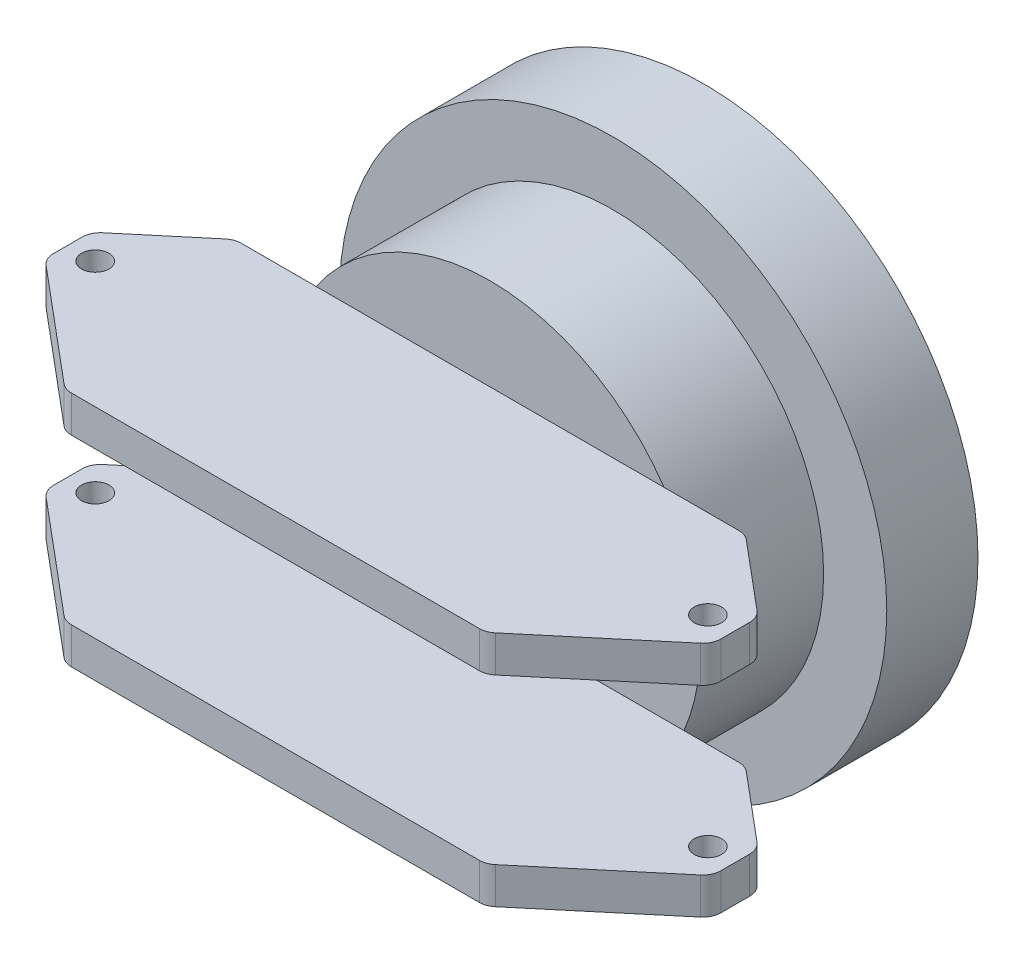
SolidWorks part; units mm, degrees
material "AISI 347 Annealed Stainless Steel (SS)"
ref_plane "Front" through (0, 0, 0) normal (0, 0, 1) x (1, 0, 0)
ref_plane "Top" through (0, 0, 0) normal (0, 1, 0) x (1, 0, 0)
ref_plane "Right" through (0, 0, 0) normal (1, 0, 0) x (0, 0, -1)
sketch "Sketch1" plane through (0, 0, 0) normal (0, 0, 1) x (1, 0, 0)
  circle A0 centre (0, 0) radius 30
  dimension "D1" = 60
extrude "Boss-Extrude1" add sketch "Sketch1" along normal blind 10
sketch "Sketch2" plane through (0, 0, 10) normal (0, 0, 1) x (1, 0, 0)
  circle A0 centre (0, 0) radius 23.08
extrude "Boss-Extrude2" add sketch "Sketch2" along normal blind 13.4862 contours A0
ref_plane "Plane1" through (0, 13, 0) normal (0, 1, 0) x (1, 0, 0)
sketch "Sketch4" plane through (0, 13, 0) normal (0, 1, 0) x (1, 0, 0)
  line L0 (0, -23.4862) -> (-48.9101, -23.4862) construction
  line L1 (-23.08, -23.4862) -> (23.08, -23.4862) construction
  line L2 (28, -23.4862) -> (-28, -23.4862)
  line L3 (-28, -23.4862) -> (-36.5797, -30.6854)
  line L4 (-36.5797, -30.6854) -> (-36.5797, -35.6854)
  line L5 (-23.08, -23.4862) -> (-23.08, -83.02) construction
  line L6 (-23.08, -10) -> (-23.08, -23.4862) construction
  line L7 (-36.5797, -35.6854) -> (-23.08, -47.013)
  line L8 (-36.5797, -35.6854) -> (-36.5797, -54.4246) construction
  line L9 (-23.08, -47.013) -> (23.08, -47.013)
  line L10 (0, -23.4862) -> (0, -50.8219) construction
  line L11 (36.5797, -35.6854) -> (23.08, -47.013)
  line L12 (36.5797, -30.6854) -> (36.5797, -35.6854)
  line L13 (28, -23.4862) -> (36.5797, -30.6854)
  point P17 (0, -47.013)
  dimension "D1" = 28
  dimension "D2" = 40
  dimension "D3" = 5
  dimension "D4" = 11.2
  dimension "D5" = 50
extrude "Boss-Extrude3" add sketch "Sketch4" against normal blind 4
fillet "Fillet1" radius 2 8 edges at (-28, 11, 23.4862) (28, 11, 23.4862) (36.5797, 11, 30.6854) (36.5797, 11, 35.6854) (23.08, 11, 47.013) (-23.08, 11, 47.013) (-36.5797, 11, 35.6854) (-36.5797, 11, 30.6854)
sketch "Sketch5" plane through (0, 13, 0) normal (0, 1, 0) x (1, 0, 0)
  line L0 (-36.5797, -33.1854) -> (-33.5797, -33.1854) construction
  line L1 (-36.5797, -31.618) -> (-36.5797, -34.7528) construction
  circle A0 centre (-33.5797, -33.1854) radius 1.5
  dimension "D2" = 3
  dimension "D1" = 3
extrude "Cut-Extrude1" cut sketch "Sketch5" against normal blind 4
mirror "Mirror1" about plane through (0, 0, 0) normal (1, 0, 0) of "Cut-Extrude1"
mirror "Mirror2" about plane through (0, 0, 0) normal (0, 1, 0) of "Mirror1", "Cut-Extrude1", "Fillet1", "Boss-Extrude3"
sketch "Sketch8" plane through (0, 0, 0) normal (0, 0, -1) x (-1, 0, 0)
  circle A0 centre (0, 0) radius 15
  dimension "D1" = 30
ref_plane "Plane2" through (0, 0, -35) normal (0, 0, -1) x (-1, 0, 0)
sketch "Sketch9" plane through (0, 0, -35) normal (0, 0, -1) x (-1, 0, 0)
  line L0 (-100, 0) -> (0, 0) construction
  line L1 (0, 0) -> (0, 100) construction
  text T0 "X5\r\n" font "Century Gothic" height 20
  text T1 "Y5\r\n\r\n" font "Century Gothic" height 20
  dimension "D1" = 100
sketch "Sketch10" plane through (0, 0, 0) normal (0, 1, 0) x (1, 0, 0)
  line L0 (0, 35) -> (0, -65) construction
  line L1 (100, 35) -> (0, 35) construction
  text T0 "Z5" font "Century Gothic" height 20
ref_plane "Plane3" through (0, 0, 105) normal (0, 0, -1) x (-1, 0, 0)
sketch "Sketch11" plane through (0, 0, 105) normal (0, 0, -1) x (-1, 0, 0)
  line L0 (0, 100) -> (0, 0) construction
  line L1 (0, 0) -> (-100, 0) construction
  line L2 (0, 0) -> (0, 100) construction
  text T0 "X6" font "Century Gothic" height 20
  text T1 "Y6" font "Century Gothic" height 20
sketch "Sketch12" plane through (0, 0, 0) normal (1, 0, 0) x (0, 0, -1)
  line L0 (-105, 0) -> (-205, 0) construction
  line L1 (-105, 100) -> (-105, 0) construction
  text T0 "Z6" font "Century Gothic" height 20
extrude "Boss-Extrude4" add sketch "Sketch8" along normal blind 5
sketch "Sketch13" plane through (0, 0, -5) normal (0, 0, -1) x (-1, 0, 0)
  circle A0 centre (0, 0) radius 2.5
  dimension "D1" = 5
extrude "Boss-Extrude6" add sketch "Sketch13" along normal blind 10
sketch "Sketch15" plane through (0, 0, 105) normal (0, 0, -1) x (-1, 0, 0)
  point P0 (0, 0)
